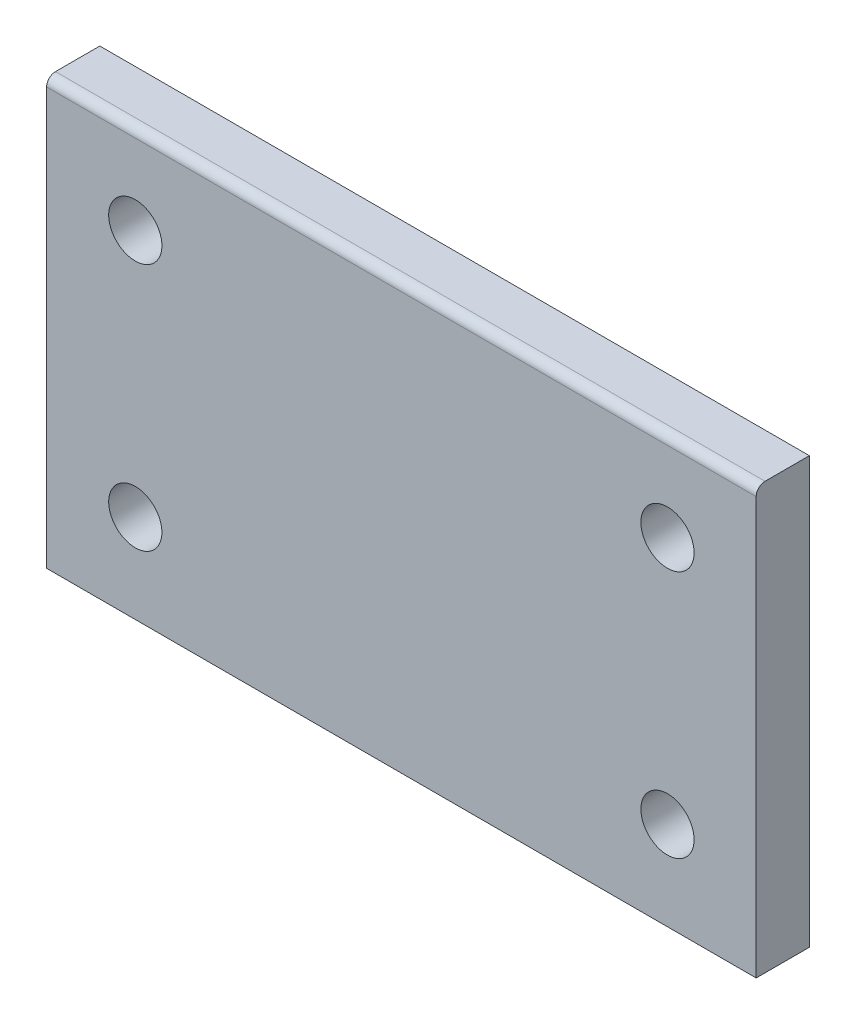
SolidWorks part; units mm, degrees
ref_plane "Front Plane" through (0, 0, 0) normal (0, 0, 1) x (1, 0, 0)
ref_plane "Top Plane" through (0, 0, 0) normal (0, 1, 0) x (1, 0, 0)
ref_plane "Right Plane" through (0, 0, 0) normal (1, 0, 0) x (0, 0, -1)
sketch "Sketch1" plane through (0, 0, 0) normal (0, 0, 1) x (1, 0, 0)
  line L1 (0, 0) -> (127, 0)
  line L2 (0, 0) -> (0, 76.2)
  line L3 (0, 76.2) -> (127, 76.2)
  line L4 (127, 0) -> (127, 76.2)
extrude "base" add sketch "Sketch1" along normal blind 9.525
sketch "Sketch2" plane through (0, 0, 0) normal (0, 0, 1) x (1, 0, 0)
  circle A0 centre (15.875, 15.875) radius 4.7625
  circle A1 centre (111.125, 15.875) radius 4.7625
  circle A2 centre (15.875, 60.325) radius 4.7625
  circle A3 centre (111.125, 60.325) radius 4.7625
extrude "holes" cut sketch "Sketch2" along normal through all
fillet "Fillet2" radius 1.5875 1 edges at (63.5, 76.2, 9.525)
